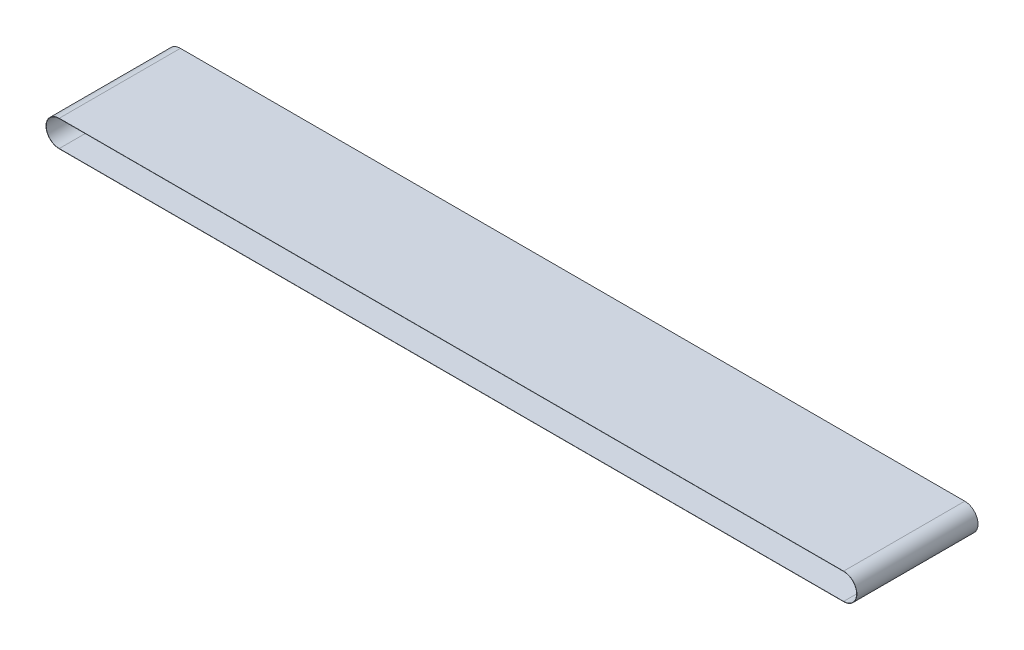
SolidWorks part; units mm, degrees
ref_plane "Front" through (0, 0, 0) normal (0, 0, 1) x (1, 0, 0)
ref_plane "Top" through (0, 0, 0) normal (0, 1, 0) x (1, 0, 0)
ref_plane "Right" through (0, 0, 0) normal (1, 0, 0) x (0, 0, -1)
sketch "草图2" plane through (0, 0, 0) normal (0, 0, 1) x (1, 0, 0)
  line L0 (0, 0) -> (1, 0) construction
  line L1 (0, 0) -> (0, 1) construction
  line L2 (0, -165) -> (-9873.2761, -165)
  line L3 (-9873.2761, 165) -> (0, 165)
  arc A0 (0, 165) -> (0, -165) centre (0, 0) cw
  arc A1 (-9873.2761, -165) -> (-9873.2761, 165) centre (-9873.2761, 0) cw
sketch "草图3" plane through (0, 0, 0) normal (1, 0, 0) x (0, 0, -1)
  line L1 (-762.5, 166.5) -> (762.5, 166.5)
  line L2 (-762.5, 166.5) -> (-762.5, 163.5)
  line L3 (-762.5, 163.5) -> (762.5, 163.5)
  line L4 (762.5, 166.5) -> (762.5, 163.5)
  line L5 (-762.5, 166.5) -> (762.5, 163.5) construction
  line L6 (-762.5, 163.5) -> (762.5, 166.5) construction
  point P0 (0, 165)
  point P6 (0, 166.5)
  dimension "D1" = 1525
  dimension "D2" = 3
sweep "扫描1" add profiles "草图3" path "草图2"
